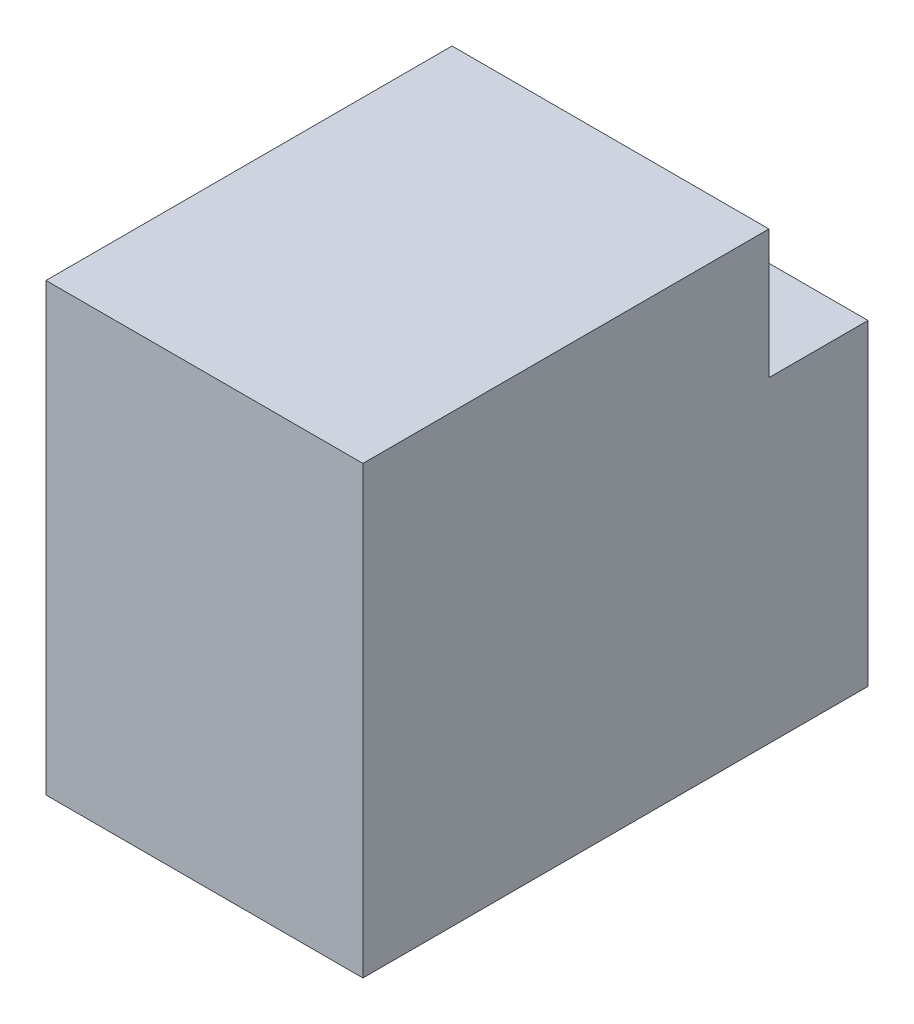
SolidWorks part; units mm, degrees
ref_plane "Front Plane" through (0, 0, 0) normal (0, 0, 1) x (1, 0, 0)
ref_plane "Top Plane" through (0, 0, 0) normal (0, 1, 0) x (1, 0, 0)
ref_plane "Right Plane" through (0, 0, 0) normal (1, 0, 0) x (0, 0, -1)
sketch "Sketch1" plane through (0, 0, 0) normal (0, 0, 1) x (1, 0, 0)
  line L1 (16, 16) -> (-16, 16)
  line L2 (16, 16) -> (16, -16)
  line L3 (16, -16) -> (-16, -16)
  line L4 (-16, 16) -> (-16, -16)
  line L5 (16, 16) -> (-16, -16) construction
  line L6 (16, -16) -> (-16, 16) construction
  point P0 (0, 0)
  dimension "D1" = 32
extrude "Boss-Extrude1" add sketch "Sketch1" along normal blind 10
sketch "Sketch2" plane through (0, 0, 10) normal (0, 0, 1) x (1, 0, 0)
  line L1 (-16, -16) -> (16, -16)
  line L2 (-16, -16) -> (-16, 29)
  line L3 (-16, 29) -> (16, 29)
  line L4 (16, -16) -> (16, 29)
  line L5 (-16, -16) -> (16, 29) construction
  line L6 (-16, 29) -> (16, -16) construction
  point P4 (0, 6.5)
  dimension "D1" = 45
  dimension "D2" = 32
extrude "Boss-Extrude2" add sketch "Sketch2" along normal blind 41
sketch "Sketch3" plane through (0, 0, 0) normal (0, 0, -1) x (-1, 0, 0)
  line L1 (12, 12) -> (-12, 12) construction
  line L2 (12, 12) -> (12, -12) construction
  line L3 (12, -12) -> (-12, -12) construction
  line L4 (-12, 12) -> (-12, -12) construction
  line L5 (12, 12) -> (-12, -12) construction
  line L6 (12, -12) -> (-12, 12) construction
  circle A0 centre (-12, 12) radius 1.6
  circle A1 centre (-12, -12) radius 1.6
  circle A2 centre (12, 12) radius 1.6
  circle A3 centre (12, -12) radius 1.6
  circle A4 centre (0, 0) radius 6.5
  point P0 (0, 0)
  dimension "D2" = 3.2
  dimension "D3" = 13
  dimension "D1" = 24
extrude "Cut-Extrude1" cut sketch "Sketch3" against normal blind 10
